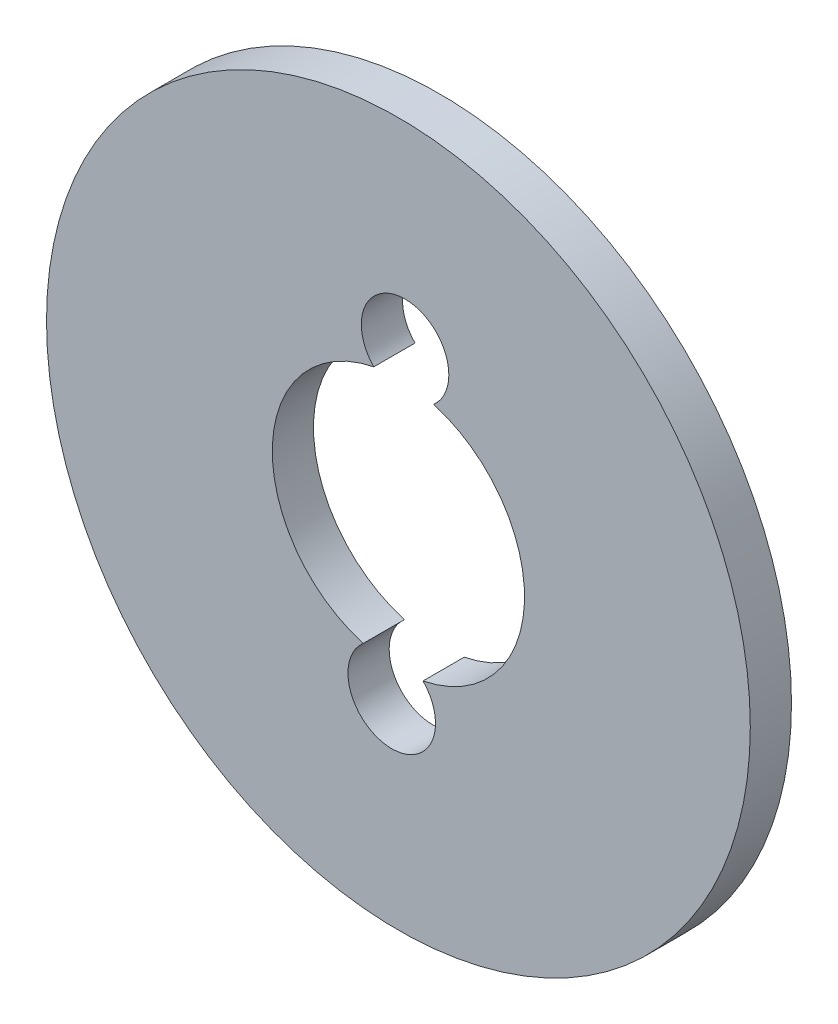
SolidWorks part; units mm, degrees
ref_plane "Plan de face" through (0, 0, 0) normal (0, 0, 1) x (1, 0, 0)
ref_plane "Plan de dessus" through (0, 0, 0) normal (0, 1, 0) x (1, 0, 0)
ref_plane "Plan de droite" through (0, 0, 0) normal (1, 0, 0) x (0, 0, -1)
sketch "Esquisse1" plane through (0, 0, 0) normal (0, 0, 1) x (1, 0, 0)
  circle A0 centre (0, 0) radius 6.8356
  circle A1 centre (0, 0) radius 2.45
  circle A2 centre (0, 0) radius 5.3356 construction
  dimension "D1" = 1.5
  dimension "D2" = 4.9
extrude "Boss.-Extru.1" add sketch "Esquisse1" against normal blind 0.8
sketch "Esquisse3" plane through (0, 0, -0.8) normal (0, 0, -1) x (-1, 0, 0)
  circle A0 centre (-0.1295, 2.9972) radius 0.85
  circle A1 centre (0.1295, -2.9972) radius 0.85
  dimension "D1" = 1.7
extrude "Enlèv. mat.-Extru.1" cut sketch "Esquisse3" against normal through all
